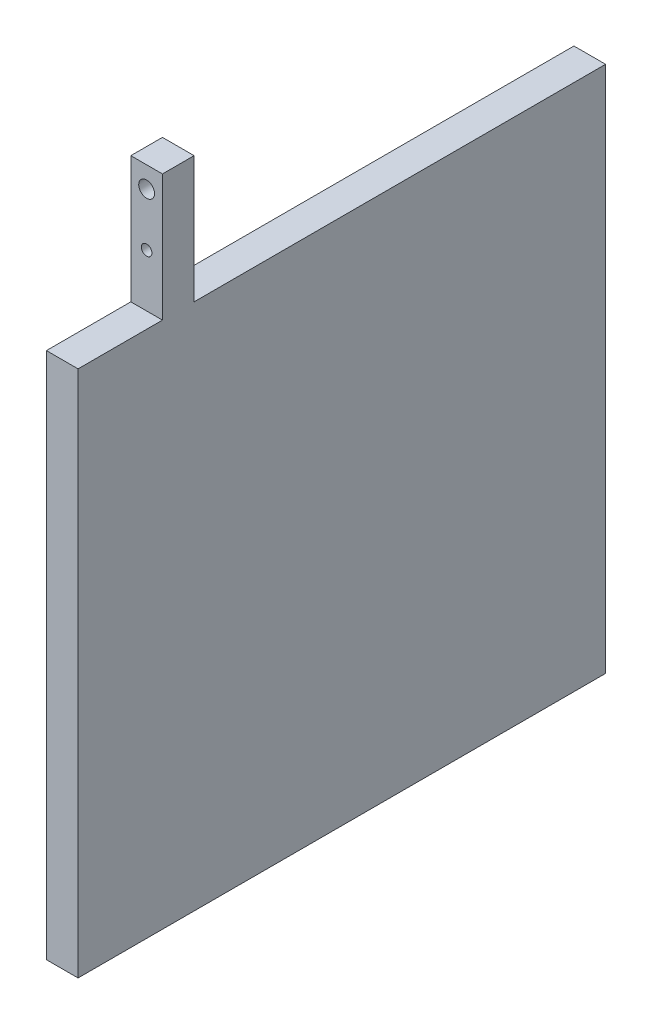
SolidWorks part; units mm, degrees
material "Perspex (TM) GS Acrylic Cast Sheet"
ref_plane "Front Plane" through (0, 0, 0) normal (0, 0, 1) x (1, 0, 0)
ref_plane "Top Plane" through (0, 0, 0) normal (0, 1, 0) x (1, 0, 0)
ref_plane "Right Plane" through (0, 0, 0) normal (1, 0, 0) x (0, 0, -1)
sketch "Sketch1" plane through (0, 0, 0) normal (1, 0, 0) x (0, 0, -1)
  line L0 (0, 0) -> (0, -12)
  line L1 (0, -12) -> (-8, -12)
  line L2 (-8, -12) -> (-8, -62)
  line L3 (-8, -62) -> (42, -62)
  line L4 (42, -62) -> (42, -12)
  line L5 (42, -12) -> (3, -12)
  line L6 (3, -12) -> (3, 0)
  line L7 (3, 0) -> (0, 0)
  dimension "D1" = 50
  dimension "D2" = 50
  dimension "D3" = 3
  dimension "D4" = 8
  dimension "D5" = 12
extrude "Boss-Extrude1" add sketch "Sketch1" along normal blind 3
sketch "Sketch2" plane through (0, 0, 0) normal (0, 0, 1) x (1, 0, 0)
  line L0 (3, 0) -> (0, 0) construction
  circle A0 centre (1.5, -2) radius 0.75
  circle A1 centre (1.5, -7) radius 0.5
  point P2 (1.5, 0)
  point P3 (0, 0)
  dimension "D2" = 1.5
  dimension "D4" = 1
  dimension "D1" = 2
  dimension "D3" = 5
extrude "Cut-Extrude1" cut sketch "Sketch2" against normal blind 10
